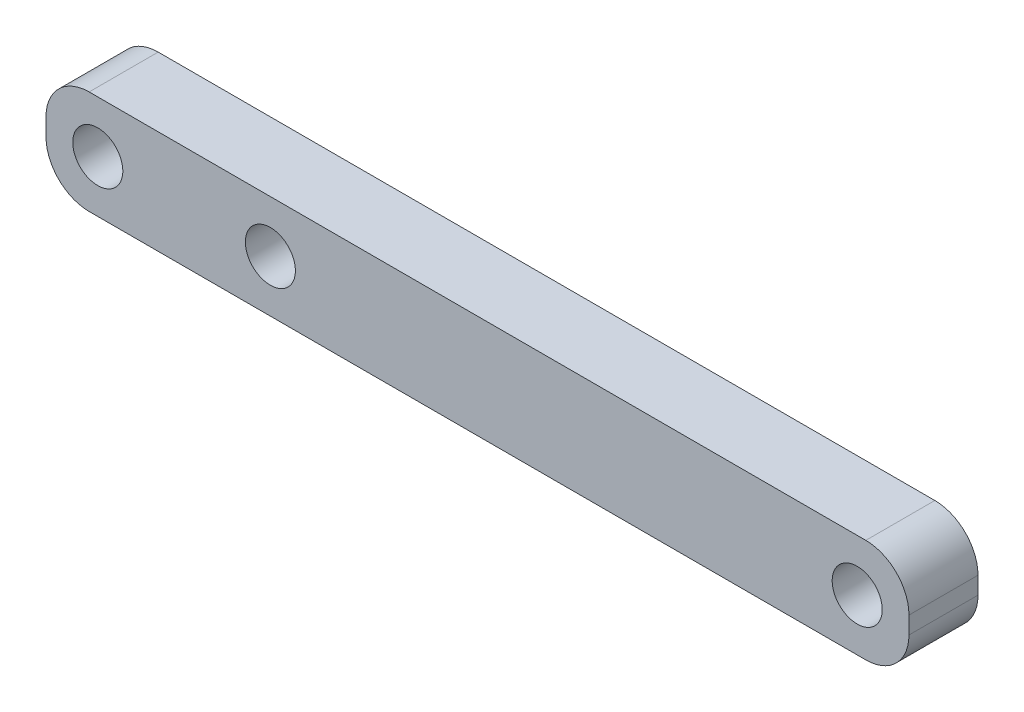
SolidWorks part; units mm, degrees
ref_plane "Front" through (0, 0, 0) normal (0, 0, 1) x (1, 0, 0)
ref_plane "Top" through (0, 0, 0) normal (0, 1, 0) x (1, 0, 0)
ref_plane "Right" through (0, 0, 0) normal (1, 0, 0) x (0, 0, -1)
sketch "Sketch1" plane through (0, 0, 0) normal (0, 0, 1) x (1, 0, 0)
  line L1 (0, 0) -> (-50, 0)
  line L2 (0, 0) -> (0, -6)
  line L3 (0, -6) -> (-50, -6)
  line L4 (-50, 0) -> (-50, -6)
  dimension "D1" = 6
  dimension "D2" = 50
extrude "Boss-Extrude1" add sketch "Sketch1" along normal blind 4
sketch "Sketch2" plane through (0, 0, 0) normal (0, 0, -1) x (-1, 0, 0)
  line L0 (50, -6) -> (0, -6) construction
  line L1 (0, -6) -> (0, 0) construction
  line L2 (50, 0) -> (50, -6) construction
  circle A0 centre (3, -3) radius 1.45
  circle A1 centre (37, -3) radius 1.45
  dimension "D1" = 2.9
  dimension "D2" = 2.9
  dimension "D3" = 3
  dimension "D4" = 3
  dimension "D5" = 3
  dimension "D6" = 13
extrude "Cut-Extrude1" cut sketch "Sketch2" against normal through all
fillet "Fillet1" radius 2.5 4 edges at (-50, -6, 2) (-50, 0, 2) (0, -6, 2) (0, 0, 2)
sketch "Sketch3" plane through (0, 0, 0) normal (0, 0, -1) x (-1, 0, 0)
  line L0 (2.5, 0) -> (47.5, 0) construction
  line L1 (50, -2.5) -> (50, -3.5) construction
  circle A0 centre (47, -3) radius 1.45
  dimension "D1" = 2.9
  dimension "D2" = 3
  dimension "D3" = 3
extrude "Cut-Extrude2" cut sketch "Sketch3" against normal through all
